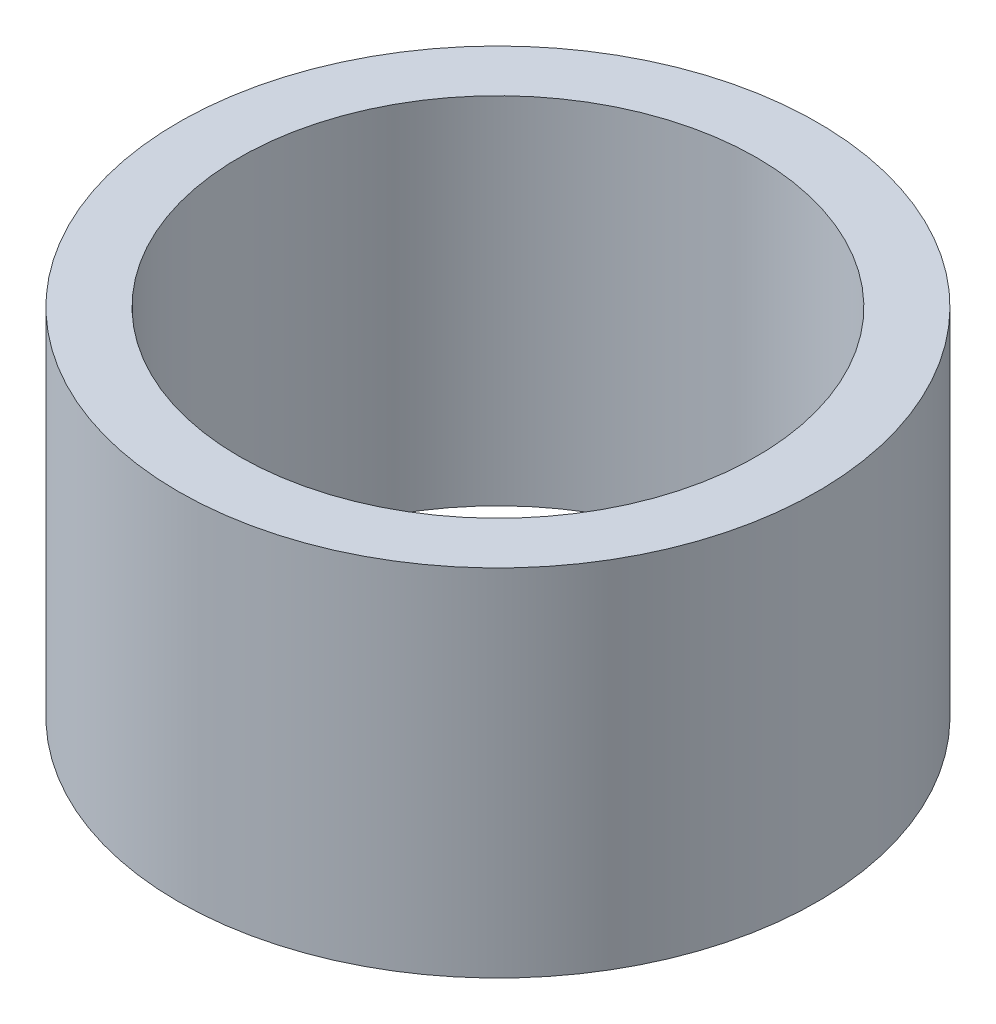
SolidWorks part; units mm, degrees
ref_plane "Front Plane" through (0, 0, 0) normal (0, 0, 1) x (1, 0, 0)
ref_plane "Top Plane" through (0, 0, 0) normal (0, 1, 0) x (1, 0, 0)
ref_plane "Right Plane" through (0, 0, 0) normal (1, 0, 0) x (0, 0, -1)
sketch "Sketch1" plane through (0, 0, 0) normal (0, 1, 0) x (1, 0, 0)
  circle A0 centre (0, 0) radius 2.55
  circle A1 centre (0, 0) radius 3.15
  dimension "D1" = 5.1
  dimension "D2" = 6.3
extrude "Boss-Extrude1" add sketch "Sketch1" along normal blind 3.5
